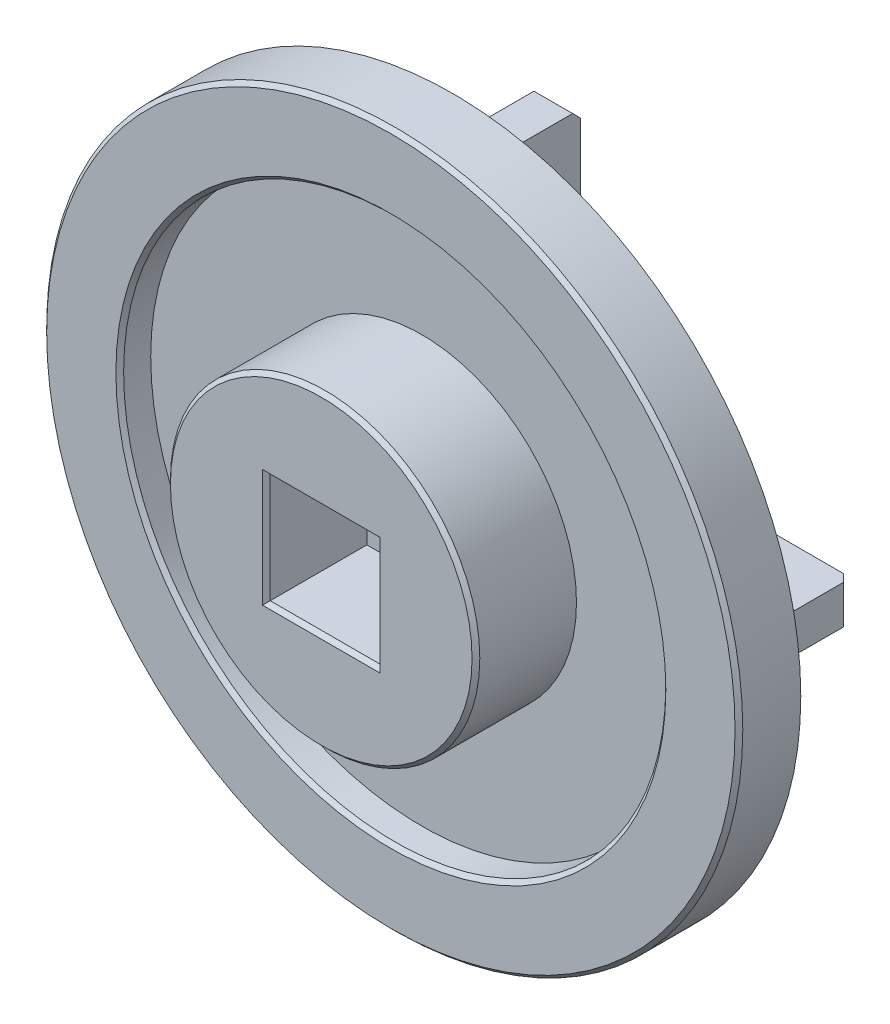
SolidWorks part; units mm, degrees
ref_plane "Front" through (0, 0, 0) normal (0, 0, 1) x (1, 0, 0)
ref_plane "Top" through (0, 0, 0) normal (0, 1, 0) x (1, 0, 0)
ref_plane "Right" through (0, 0, 0) normal (1, 0, 0) x (0, 0, -1)
sketch "Sketch1" plane through (0, 0, 0) normal (0, 0, 1) x (1, 0, 0)
  circle A0 centre (0, 0) radius 45
  dimension "D1" = 90
extrude "Boss-Extrude1" add sketch "Sketch1" along normal blind 8
sketch "Sketch2" plane through (0, 0, 8) normal (0, 0, 1) x (1, 0, 0)
  circle A0 centre (0, 0) radius 35.05
  dimension "D1" = 70.1
extrude "Cut-Extrude1" cut sketch "Sketch2" against normal blind 4
sketch "Sketch3" plane through (0, 0, 4) normal (0, 0, 1) x (1, 0, 0)
  line L0 (0, 0) -> (7.1, 0) construction
  line L1 (-7.1, 7.1) -> (7.1, 7.1)
  line L2 (-7.1, 7.1) -> (-7.1, -7.1)
  line L3 (-7.1, -7.1) -> (7.1, -7.1)
  line L4 (7.1, 7.1) -> (7.1, -7.1)
  line L5 (0, 0) -> (-7.1, 0) construction
  circle A0 centre (0, 0) radius 20
  dimension "D1" = 40
  dimension "D2" = 14.2
extrude "Boss-Extrude2" add sketch "Sketch3" along normal blind 13
chamfer "Chamfer1" distance 0.5 angle 45 7 edges at (0, -7.1, 17) (-7.1, 0, 17) (0, 7.1, 17) (7.1, 0, 17) (20, 0, 17) (35.05, 0, 8) (45, 0, 8)
sketch "Sketch4" plane through (0, 0, 0) normal (0, 0, -1) x (-1, 0, 0)
  line L0 (-2.5, 2.5) -> (-37.5, 2.5)
  line L1 (2.5, 37.5) -> (-2.5, 37.5)
  line L2 (2.5, 37.5) -> (2.5, 2.5)
  line L3 (2.5, -37.5) -> (-2.5, -37.5)
  line L4 (-2.5, 37.5) -> (-2.5, 2.5)
  line L5 (37.5, 2.5) -> (2.5, 2.5)
  line L6 (37.5, 2.5) -> (37.5, -2.5)
  line L7 (37.5, -2.5) -> (2.5, -2.5)
  line L8 (-37.5, 2.5) -> (-37.5, -2.5)
  line L9 (2.5, -2.5) -> (2.5, -37.5)
  line L10 (-2.5, -2.5) -> (-2.5, -37.5)
  line L11 (-2.5, -2.5) -> (-37.5, -2.5)
  line L12 (-2.5, 2.5) -> (2.5, -2.5) construction
  point P12 (0, 0)
  dimension "D1" = 35
  dimension "D2" = 5
extrude "Boss-Extrude3" add sketch "Sketch4" along normal blind 14
chamfer "Chamfer3" distance 1 angle 45 4 edges at (0, -37.5, -14) (-37.5, 0, -14) (0, 37.5, -14) (37.5, 0, -14)
fillet "Fillet1" radius 1 4 edges at (2.5, 2.5, -7) (-2.5, 2.5, -7) (-2.5, -2.5, -7) (2.5, -2.5, -7)
